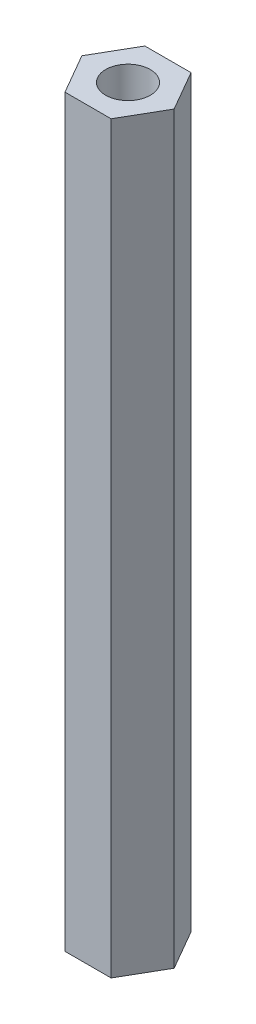
SolidWorks part; units mm, degrees
material "Aleación 6061"
ref_plane "Alzado" through (0, 0, 0) normal (0, 0, 1) x (1, 0, 0)
ref_plane "Planta" through (0, 0, 0) normal (0, 1, 0) x (1, 0, 0)
ref_plane "Vista lateral" through (0, 0, 0) normal (1, 0, 0) x (0, 0, -1)
sketch "Croquis1" plane through (0, 0, 0) normal (0, 1, 0) x (1, 0, 0)
  line L1 (3.1, 0) -> (1.55, 2.6847)
  line L2 (1.55, 2.6847) -> (-1.55, 2.6847)
  line L3 (-1.55, 2.6847) -> (-3.1, 0)
  line L4 (-3.1, 0) -> (-1.55, -2.6847)
  line L5 (-1.55, -2.6847) -> (1.55, -2.6847)
  line L6 (1.55, -2.6847) -> (3.1, 0)
  circle A0 centre (0, 0) radius 2.6847 construction
  dimension "D1" = 6.2
extrude "Saliente-Extruir1" add sketch "Croquis1" along normal blind 50
sketch "Croquis2" plane through (0, 50, 0) normal (0, 1, 0) x (1, 0, 0)
  circle A0 centre (0, 0) radius 1.5
  dimension "D1" = 3
extrude "Cortar-Extruir1" cut sketch "Croquis2" against normal blind 10
sketch "Croquis3" plane through (0, 0, 0) normal (0, -1, 0) x (1, 0, 0)
  circle A0 centre (0, 0) radius 1.5
  dimension "D1" = 3
extrude "Cortar-Extruir2" cut sketch "Croquis3" against normal blind 10
